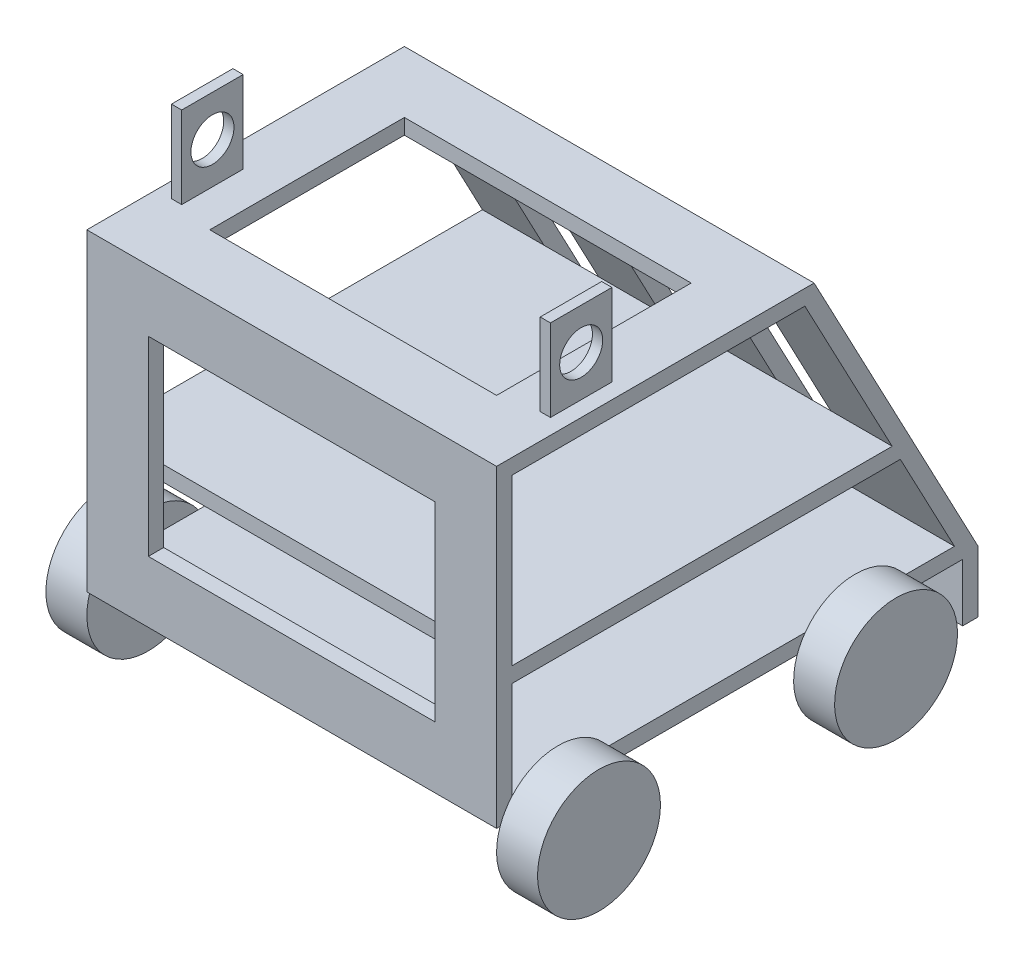
SolidWorks part; units mm, degrees
ref_plane "Front Plane" through (0, 0, 0) normal (0, 0, 1) x (1, 0, 0)
ref_plane "Top Plane" through (0, 0, 0) normal (0, 1, 0) x (1, 0, 0)
ref_plane "Right Plane" through (0, 0, 0) normal (1, 0, 0) x (0, 0, -1)
ref_plane "LeftFrame" through (63.5, 0, 0) normal (1, 0, 0) x (0, 0, -1)
sketch "Sketch2" plane through (63.5, 0, 0) normal (1, 0, 0) x (0, 0, -1)
  line L0 (-19.05, -25.4) -> (-19.05, 25.4)
  line L1 (-19.05, 25.4) -> (19.05, 25.4)
  line L2 (19.05, 25.4) -> (19.05, -25.4)
  line L3 (19.05, -25.4) -> (-19.05, -25.4)
  circle A0 centre (0, 0) radius 13.335
  point P5 (0, -25.4)
  point P8 (-19.05, 0)
  dimension "D1" = 26.67
  dimension "D2" = 50.8
  dimension "D3" = 38.1
ref_plane "RightFrame" through (292.1, 0, 0) normal (1, 0, 0) x (0, 0, -1)
ref_plane "Middle" through (177.8, 0, 0) normal (1, 0, 0) x (0, 0, -1)
sketch "Sketch4" plane through (292.1, 0, -263.652) normal (-1, 0, 0) x (0, 0, 1)
  line L0 (244.602, -25.4) -> (244.602, 25.4)
  line L1 (244.602, 25.4) -> (282.702, 25.4)
  line L2 (282.702, 25.4) -> (282.702, -25.4)
  line L3 (282.702, -25.4) -> (244.602, -25.4)
  circle A0 centre (263.652, 0) radius 13.335
  point P5 (263.652, -25.4)
  point P8 (244.602, 0)
  dimension "D1" = 26.67
  dimension "D2" = 50.8
  dimension "D3" = 38.1
extrude "Boss-Extrude2" add sketch "Sketch2" along normal mid plane 6.35
extrude "Boss-Extrude3" add sketch "Sketch4" along normal mid plane 6.35 separate body
sketch "Sketch6" plane through (177.8, 0, 0) normal (1, 0, 0) x (0, 0, -1)
  line L0 (-19.05, -25.4) -> (-61.976, -25.4)
  line L1 (-61.976, -25.4) -> (-61.976, -255.524)
  line L2 (-61.976, -255.524) -> (236.474, -255.524)
  line L3 (236.474, -255.524) -> (236.474, -217.424)
  line L4 (236.474, -217.424) -> (134.874, -25.4)
  line L5 (134.874, -25.4) -> (19.05, -25.4)
  line L6 (-61.976, 61.976) -> (61.976, 61.976) construction
  line L7 (-61.976, -61.976) -> (61.976, -61.976) construction
  line L11 (-19.05, -25.4) -> (19.05, -25.4)
  line L12 (19.05, -25.4) -> (19.05, 25.4)
  line L13 (19.05, 25.4) -> (-19.05, 25.4)
  line L14 (-19.05, 25.4) -> (-19.05, -25.4)
  line L15 (-19.05, -25.4) -> (19.05, -25.4)
  dimension "D1" = 61.976
  dimension "D2" = 196.85
  dimension "D3" = 298.45
  dimension "D5" = 61.976
  dimension "D6" = 61.976
  dimension "D7" = 61.976
  dimension "D8" = 279.4
  dimension "D10" = 317.5
  dimension "D9" = 0
extrude "Boss-Extrude4" add sketch "Sketch6" along normal mid plane 254
ref_plane "Left" through (50.8, 0, 0) normal (-1, 0, 0) x (0, 0, 1)
ref_plane "Right" through (304.8, 0, 0) normal (1, 0, 0) x (0, 0, -1)
sketch "Sketch13" plane through (177.8, 0, 0) normal (1, 0, 0) x (0, 0, -1)
  line L1 (-61.976, -255.524) -> (236.474, -255.524) construction
  line L2 (-52.451, -34.925) -> (129.1376, -34.925)
  line L3 (129.1376, -34.925) -> (226.949, -219.7886)
  line L4 (226.949, -219.7886) -> (226.949, -255.524)
  line L5 (226.949, -255.524) -> (-61.976, -255.524)
  line L7 (134.874, -25.4) -> (-61.976, -25.4) construction
  line L8 (236.474, -255.524) -> (236.474, -217.424) construction
  line L9 (236.474, -217.424) -> (134.874, -25.4) construction
  line L10 (-52.451, -34.925) -> (-52.451, -219.7886)
  line L11 (-52.451, -219.7886) -> (-61.976, -219.7886)
  line L12 (-61.976, -25.4) -> (-61.976, -255.524) construction
  line L13 (-61.976, -219.7886) -> (-61.976, -255.524)
  line L14 (226.949, -219.7886) -> (249.9218, -219.7886) construction
  dimension "D1" = 9.525
  dimension "D2" = 9.525
  dimension "D3" = 9.525
  dimension "D4" = 9.525
extrude "Cut-Extrude3" cut sketch "Sketch13" against normal mid plane 254
sketch "Sketch14" plane through (177.8, 0, 0) normal (1, 0, 0) x (0, 0, -1)
  line L0 (226.949, -219.7886) -> (-52.451, -219.7886)
  line L2 (-52.451, -219.7886) -> (-52.451, -210.2636)
  line L3 (-52.451, -210.2636) -> (221.9093, -210.2636)
  line L4 (226.949, -219.7886) -> (129.1376, -34.925) construction
  line L5 (221.9093, -210.2636) -> (226.949, -219.7886)
  line L6 (-52.451, -34.925) -> (-52.451, -219.7886) construction
  line L7 (-52.451, -146.7636) -> (188.3114, -146.7636)
  line L8 (188.3114, -146.7636) -> (183.2718, -137.2386)
  line L9 (183.2718, -137.2386) -> (-52.451, -137.2386)
  line L10 (-52.451, -137.2386) -> (-52.451, -146.7636)
  dimension "D1" = 9.525
  dimension "D2" = 63.5
  dimension "D3" = 9.525
extrude "Boss-Extrude7" add sketch "Sketch14" along normal mid plane 254
sketch "Sketch16" plane through (304.8, 0, 0) normal (1, 0, 0) x (0, 0, -1)
  line L0 (-61.976, -25.4) -> (-61.976, -219.7886) construction
  line L1 (236.474, -255.524) -> (236.474, -217.424) construction
  line L2 (-61.976, -219.7886) -> (226.949, -219.7886) construction
  circle A0 centre (-23.876, -232.4886) radius 38.1
  circle A1 centre (160.274, -232.4886) radius 38.1
  dimension "D1" = 76.2
  dimension "D2" = 76.2
  dimension "D3" = 38.1
  dimension "D4" = 76.2
  dimension "D5" = 12.7
extrude "Boss-Extrude8" add sketch "Sketch16" along normal blind 25.4
mirror "Mirror1" about plane through (177.8, 0, 0) normal (1, 0, 0) of "Boss-Extrude8"
ref_plane "Plane8" through (0, 0, -236.474) normal (0, 0, -1) x (-1, 0, 0)
sketch "Sketch19" plane through (0, 0, -236.474) normal (0, 0, -1) x (-1, 0, 0)
  line L0 (-304.8, -217.424) -> (-304.8, -25.4) construction
  line L1 (-266.7, -63.5) -> (-232.8333, -63.5)
  line L2 (-266.7, -63.5) -> (-266.7, -179.324)
  line L3 (-266.7, -179.324) -> (-232.8333, -179.324)
  line L4 (-232.8333, -63.5) -> (-232.8333, -179.324)
  line L5 (-194.7333, -63.5) -> (-160.8667, -63.5)
  line L6 (-194.7333, -63.5) -> (-194.7333, -179.324)
  line L7 (-194.7333, -179.324) -> (-160.8667, -179.324)
  line L8 (-160.8667, -63.5) -> (-160.8667, -179.324)
  line L9 (-122.7667, -63.5) -> (-88.9, -63.5)
  line L10 (-122.7667, -63.5) -> (-122.7667, -179.324)
  line L11 (-122.7667, -179.324) -> (-88.9, -179.324)
  line L12 (-88.9, -63.5) -> (-88.9, -179.324)
  line L14 (-304.8, -25.4) -> (-50.8, -25.4) construction
  line L15 (-304.8, -217.424) -> (-50.8, -217.424) construction
  dimension "D1" = 38.1
  dimension "D2" = 33.8667
  dimension "D3" = 38.1
  dimension "D4" = 38.1
  dimension "D5" = 38.1
  dimension "D6" = 38.1
extrude "Cut-Extrude6" cut sketch "Sketch19" against normal up to surface (92.2174 mm away)
sketch "Sketch20" plane through (0, 0, 0) normal (0, 1, 0) x (1, 0, 0)
  line L3 (304.8, -61.976) -> (50.8, -61.976) construction
  line L4 (50.8, 134.874) -> (50.8, -61.976) construction
  line L5 (88.9, 96.774) -> (266.7, 96.774)
  line L6 (88.9, 96.774) -> (88.9, -23.876)
  line L7 (88.9, -23.876) -> (266.7, -23.876)
  line L8 (266.7, 96.774) -> (266.7, -23.876)
  line L17 (304.8, 134.874) -> (304.8, -61.976) construction
  line L18 (304.8, 134.874) -> (50.8, 134.874) construction
  point P4 (261.3079, -26.4946)
  dimension "D1" = 38.1
  dimension "D2" = 38.1
  dimension "D3" = 38.1
  dimension "D4" = 38.1
extrude "Cut-Extrude7" cut sketch "Sketch20" against normal up to surface (34.925 mm away) up to face at (177.8, -34.925, -38.3433)
ref_plane "Plane9" through (0, 0, 61.976) normal (0, 0, 1) x (1, 0, 0)
sketch "Sketch22" plane through (0, 0, 61.976) normal (0, 0, 1) x (1, 0, 0)
  line L0 (304.8, -25.4) -> (304.8, -219.7886) construction
  line L1 (88.9, -181.6886) -> (266.7, -181.6886)
  line L2 (88.9, -181.6886) -> (88.9, -63.5)
  line L3 (88.9, -63.5) -> (266.7, -63.5)
  line L4 (266.7, -181.6886) -> (266.7, -63.5)
  line L5 (50.8, -25.4) -> (50.8, -219.7886) construction
  line L6 (304.8, -25.4) -> (50.8, -25.4) construction
  line L7 (50.8, -219.7886) -> (304.8, -219.7886) construction
  dimension "D1" = 38.1
  dimension "D2" = 38.1
  dimension "D3" = 38.1
  dimension "D4" = 38.1
extrude "Cut-Extrude8" cut sketch "Sketch22" against normal up to surface (9.525 mm away) up to face at (177.8, -86.0818, 52.451)
